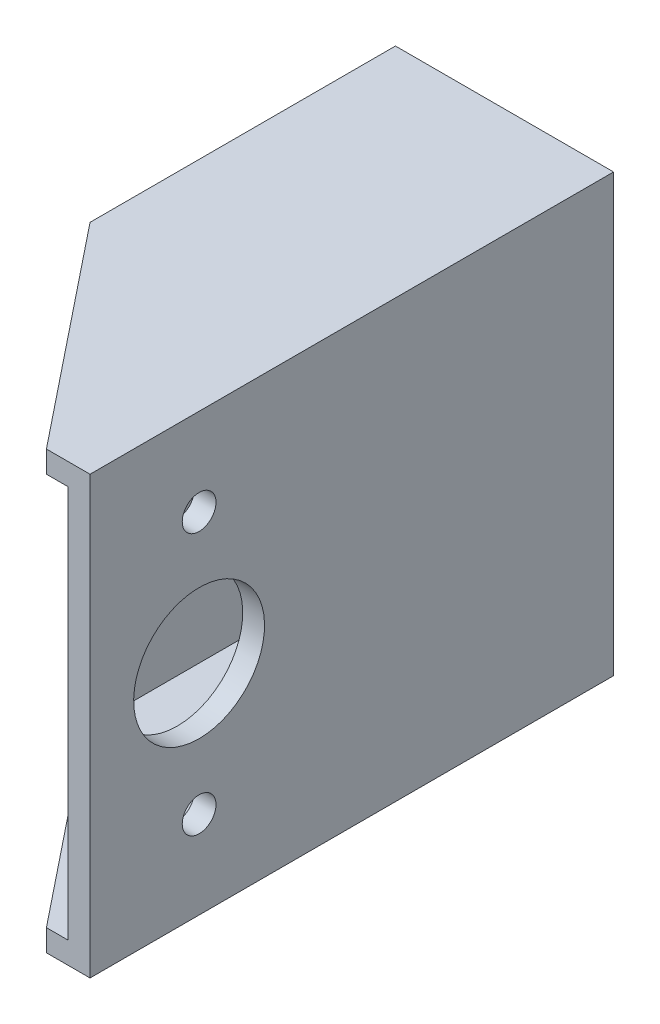
SolidWorks part; units mm, degrees
ref_plane "Front Plane" through (0, 0, 0) normal (0, 0, 1) x (1, 0, 0)
ref_plane "Top Plane" through (0, 0, 0) normal (0, 1, 0) x (1, 0, 0)
ref_plane "Right Plane" through (0, 0, 0) normal (1, 0, 0) x (0, 0, -1)
sketch "Sketch1" plane through (0, 0, 0) normal (0, 0, 1) x (1, 0, 0)
  line L1 (-12.1647, 2.5103) -> (19.5853, 2.5103)
  line L2 (-12.1647, 2.5103) -> (-12.1647, -60.9897)
  line L3 (-12.1647, -60.9897) -> (19.5853, -60.9897)
  line L4 (19.5853, 2.5103) -> (19.5853, -60.9897)
  line L5 (-8.9897, -0.6647) -> (16.4103, -0.6647)
  line L6 (-8.9897, -0.6647) -> (-8.9897, -57.8147)
  line L7 (-8.9897, -57.8147) -> (16.4103, -57.8147)
  line L8 (16.4103, -0.6647) -> (16.4103, -57.8147)
  dimension "D1" = 63.5
  dimension "D2" = 31.75
  dimension "D3" = 3.175
  dimension "D4" = 3.175
  dimension "D5" = 3.175
  dimension "D6" = 3.175
extrude "Boss-Extrude1" add sketch "Sketch1" along normal blind 76.2
sketch "Sketch2" plane through (0, 2.5103, 0) normal (0, 1, 0) x (1, 0, 0)
  line L0 (13.2353, -76.2) -> (-12.1647, -44.45)
  line L1 (19.5853, -76.2) -> (-12.1647, -76.2) construction
  line L2 (-12.1647, -76.2) -> (-12.1647, 0) construction
  line L3 (-12.1647, -44.45) -> (-12.1647, -76.2)
  line L4 (-12.1647, -76.2) -> (13.2353, -76.2)
  line L5 (13.2353, -76.2) -> (13.5724, -152.4399)
  line M4 (-12.1647, 0) -> (-12.1647, -76.2)
  line M5 (-12.1647, -76.2) -> (19.5853, -76.2)
  dimension "D1" = 31.75
  dimension "D2" = 25.4
extrude "Cut-Extrude1" cut sketch "Sketch2" against normal up to surface (63.5 mm away) contours L0 M5 M4 up to face at (3.7103, -60.9897, 38.1)
sketch "Sketch3" plane through (16.4103, 0, 0) normal (-1, 0, 0) x (0, 0, 1)
  line L0 (76.2, -57.8147) -> (76.2, -0.6647) construction
  line L1 (44.45, -60.9897) -> (76.2, -60.9897) construction
  line L2 (76.2, -29.2397) -> (48.4187, -29.2397)
  line L3 (48.4187, -57.8147) -> (48.4187, -0.6647) construction
  circle A0 centre (60.325, -29.2397) radius 9.525
  point P0 (60.325, -48.2897)
  point P9 (60.325, -10.1897)
  dimension "D3" = 15.875
  dimension "D4" = 19.05
  dimension "D1" = 15.875
  dimension "D2" = 12.7
extrude "Cut-Extrude2" cut sketch "Sketch3" against normal up to surface (3.175 mm away) contours A0 up to face at (19.5853, -29.2397, 38.1)
hole_wizard "#10 (0.1935) Diameter Hole1" positions "3DSketch1" profile "Sketch4" hole size "#10" standard "ANSI Inch" end condition through all
sketch3d "3DSketch1"
  point P0 (16.4103, -48.2897, 60.325)
  point P3 (16.4103, -10.1897, 60.325)
sketch "Sketch4" plane through (16.4103, -48.2897, 60.325) normal (0, 1, 0) x (0, 0, 1)
  line L0 (0, 0) -> (0, 3.175)
  line L1 (0, 3.175) -> (2.4574, 3.175)
  line L2 (2.4574, 3.175) -> (2.4574, 0)
  line L5 (2.4574, 0) -> (0, 0)
  line L11 (0, -6.35) -> (0, 107.95) construction
  dimension "Thru Hole Dia." = 4.9149
  dimension "Thru Hole Depth" = 3.175
